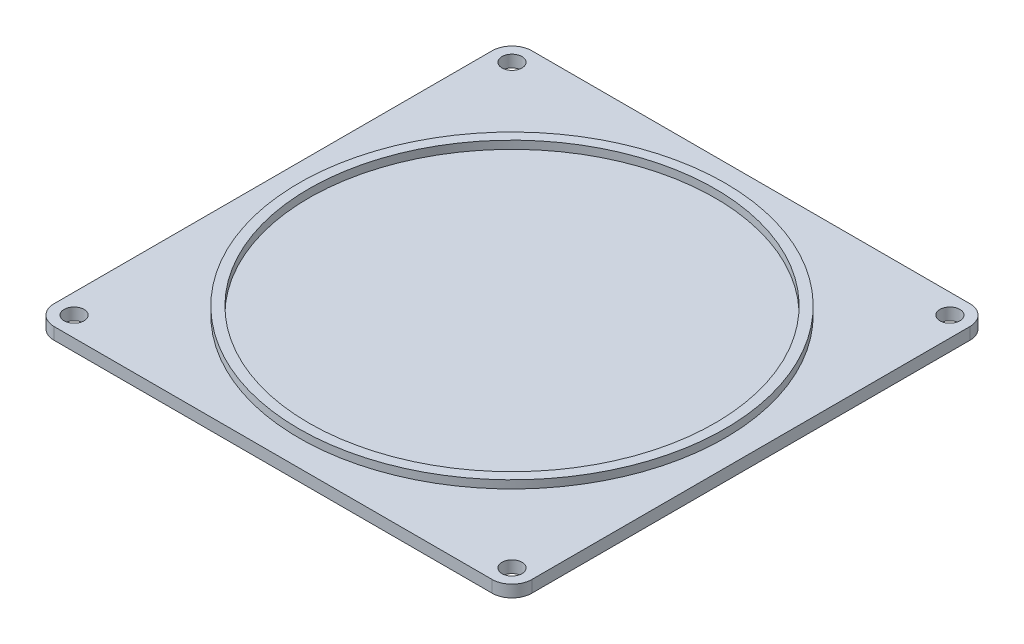
SolidWorks part; units mm, degrees
ref_plane "Front Plane" through (0, 0, 0) normal (0, 0, 1) x (1, 0, 0)
ref_plane "Top Plane" through (0, 0, 0) normal (0, 1, 0) x (1, 0, 0)
ref_plane "Right Plane" through (0, 0, 0) normal (1, 0, 0) x (0, 0, -1)
sketch "Sketch1" plane through (0, 0, 0) normal (0, 1, 0) x (1, 0, 0)
  line L1 (-60, -60) -> (60, -60)
  line L2 (-60, -60) -> (-60, 60)
  line L3 (-60, 60) -> (60, 60)
  line L4 (60, -60) -> (60, 60)
  line L5 (-60, -60) -> (60, 60) construction
  line L6 (-60, 60) -> (60, -60) construction
  point P0 (0, 0)
  dimension "D1" = 120
  dimension "D2" = 120
extrude "Boss-Extrude1" add sketch "Sketch1" along normal blind 3
sketch "Sketch2" plane through (0, 3, 0) normal (0, 1, 0) x (1, 0, 0)
  circle A0 centre (0, 0) radius 51
  circle A1 centre (0, 0) radius 53.5
  dimension "D1" = 102
  dimension "D2" = 107
extrude "Boss-Extrude2" add sketch "Sketch2" along normal blind 2
sketch "Sketch3" plane through (0, 3, 0) normal (0, 1, 0) x (1, 0, 0)
  line L0 (-60, 60) -> (-60, -60) construction
  line L1 (60, 60) -> (-60, 60) construction
  line L2 (0, 60) -> (0, -60) construction
  line L3 (-60, -60) -> (60, -60) construction
  line L4 (-60, 0) -> (60, 0) construction
  line L5 (60, -60) -> (60, 60) construction
  circle A0 centre (-55, 55) radius 2.5
  circle A1 centre (55, 55) radius 2.5
  circle A2 centre (-55, -55) radius 2.5
  circle A3 centre (55, -55) radius 2.5
  dimension "D1" = 5
  dimension "D2" = 5
  dimension "D3" = 5
extrude "Cut-Extrude1" cut sketch "Sketch3" against normal blind 3
fillet "Fillet2" radius 5 4 edges at (-60, 1.5, -60) (60, 1.5, -60) (60, 1.5, 60) (-60, 1.5, 60)
